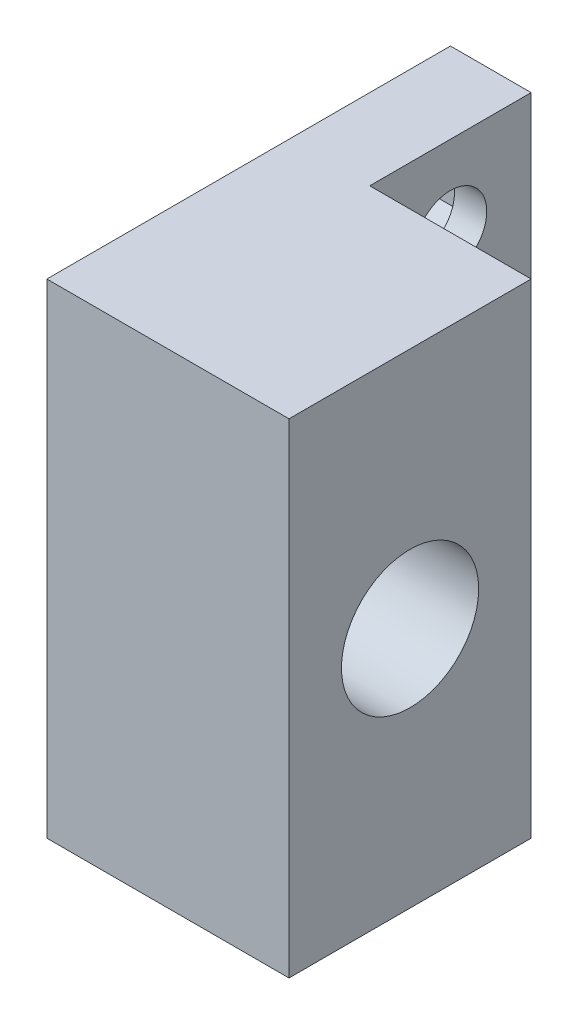
SolidWorks part; units mm, degrees
ref_plane "Front Plane" through (0, 0, 0) normal (0, 0, 1) x (1, 0, 0)
ref_plane "Top Plane" through (0, 0, 0) normal (0, 1, 0) x (1, 0, 0)
ref_plane "Right Plane" through (0, 0, 0) normal (1, 0, 0) x (0, 0, -1)
sketch "Sketch1" plane through (0, 0, 0) normal (1, 0, 0) x (0, 0, -1)
  line L0 (25, 10) -> (15, 10)
  line L1 (0, 0) -> (25, 0)
  line L2 (0, 0) -> (0, 30)
  line L3 (0, 30) -> (25, 30)
  line L4 (25, 0) -> (25, 30)
  line L5 (15, 10) -> (15, 20)
  line L6 (15, 20) -> (25, 20)
  dimension "D1" = 25
  dimension "D2" = 30
  dimension "D3" = 10
  dimension "D4" = 10
  dimension "D5" = 10
extrude "Boss-Extrude1" add sketch "Sketch1" along normal blind 5 contours L5 L6 L4 L3 L2 L1 L0
sketch "Sketch2" plane through (5, 0, 0) normal (1, 0, 0) x (0, 0, -1)
  line L0 (0, 0) -> (25, 0) construction
  line L1 (0, 30) -> (15, 30)
  line L2 (0, 30) -> (0, 0)
  line L3 (0, 0) -> (15, 0)
  line L4 (15, 30) -> (15, 0)
extrude "Boss-Extrude2" add sketch "Sketch2" along normal blind 10
sketch "Sketch3" plane through (15, 0, 0) normal (1, 0, 0) x (0, 0, -1)
  circle A0 centre (7.5, 15) radius 4.25
  dimension "D1" = 8.5
extrude "Cut-Extrude1" cut sketch "Sketch3" against normal blind 15
sketch "Sketch4" plane through (5, 0, 0) normal (1, 0, 0) x (0, 0, -1)
  circle A0 centre (20, 25) radius 2.25
  circle A1 centre (20, 5) radius 2.25
  dimension "D1" = 4.5
  dimension "D2" = 4.5
extrude "Cut-Extrude2" cut sketch "Sketch4" against normal blind 15
sketch "Sketch5" plane through (0, 0, 0) normal (-1, 0, 0) x (0, 0, 1)
  line L2 (-20, 29) -> (-23.4641, 27)
  line L3 (-23.4641, 27) -> (-23.4641, 23)
  line L4 (-23.4641, 23) -> (-20, 21)
  line L5 (-20, 21) -> (-16.5359, 23)
  line L6 (-16.5359, 23) -> (-16.5359, 27)
  line L7 (-16.5359, 27) -> (-20, 29)
  line L8 (-20, 9) -> (-23.4641, 7)
  line L9 (-23.4641, 7) -> (-23.4641, 3)
  line L10 (-23.4641, 3) -> (-20, 1)
  line L11 (-20, 1) -> (-16.5359, 3)
  line L12 (-16.5359, 3) -> (-16.5359, 7)
  line L13 (-16.5359, 7) -> (-20, 9)
  circle A0 centre (-20, 25) radius 3.4641 construction
  circle A1 centre (-20, 5) radius 3.4641 construction
  dimension "D1" = 4
  dimension "D2" = 4
extrude "Cut-Extrude3" cut sketch "Sketch5" against normal blind 3
